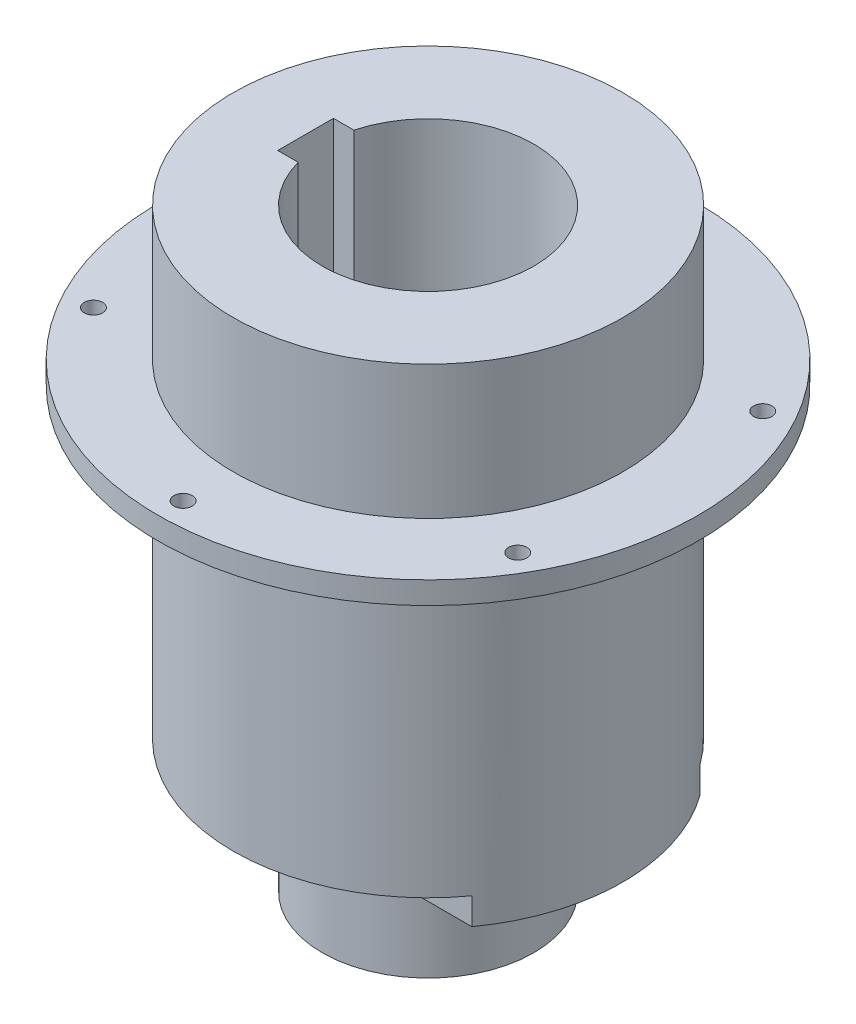
SolidWorks part; units mm, degrees
material "Steel Sectional "
ref_plane "Front Plane" through (0, 0, 0) normal (0, 0, 1) x (1, 0, 0)
ref_plane "Top Plane" through (0, 0, 0) normal (0, 1, 0) x (1, 0, 0)
ref_plane "Right Plane" through (0, 0, 0) normal (1, 0, 0) x (0, 0, -1)
sketch "Sketch1" plane through (0, 0, 0) normal (0, 0, 1) x (1, 0, 0)
  line L0 (0, 0) -> (0, 79.6401) construction
  line L1 (-6.5, 26.3) -> (-19, 26.3)
  line L2 (-19, 26.3) -> (-19, 106.8)
  line L3 (-19, 106.8) -> (-35, 106.8)
  line L4 (-35, 106.8) -> (-35, 19)
  line L5 (-19, 0) -> (-10, 0)
  line L6 (-10, 0) -> (-10, 15)
  line L7 (-10, 15) -> (-6.5, 15)
  line L8 (-6.5, 15) -> (-6.5, 26.3)
  line L9 (-35, 19) -> (-19, 19)
  line L10 (-19, 19) -> (-19, 0)
  dimension "D1" = 70
  dimension "D2" = 38
  dimension "D3" = 13
  dimension "D4" = 20
  dimension "D5" = 15
  dimension "D6" = 106.8
  dimension "D7" = 80.5
  dimension "D8" = 38
  dimension "D9" = 19
revolve "Revolve1" add sketch "Sketch1" angle 360 about L0
sketch "Sketch2" plane through (0, 106.8, 0) normal (0, 1, 0) x (1, 0, 0)
  line L1 (-22, 5) -> (-14, 5)
  line L2 (-22, 5) -> (-22, -5)
  line L3 (-22, -5) -> (-14, -5)
  line L4 (-14, 5) -> (-14, -5)
  line L5 (-22, 5) -> (-14, -5) construction
  line L6 (-22, -5) -> (-14, 5) construction
  circle A2 centre (0, 0) radius 19 construction
  point P0 (-18, 0)
  dimension "D1" = 41
  dimension "D2" = 10
  dimension "D3" = 8
extrude "Extrude1" cut sketch "Sketch2" against normal up to next
sketch "Sketch3" plane through (0, 0, 0) normal (0, 0, 1) x (1, 0, 0)
  line L0 (0, 0) -> (0, 52.8451) construction
  line L1 (-35, 78.8) -> (-48.5, 78.8)
  line L2 (-35, 106.8) -> (-35, 19) construction
  line L3 (-48.5, 78.8) -> (-48.5, 82.8)
  line L4 (-48.5, 82.8) -> (-35, 82.8)
  line L7 (-35, 82.8) -> (-35, 78.8)
  line L8 (35, 106.8) -> (-35, 106.8) construction
  dimension "D1" = 97
  dimension "D3" = 4
  dimension "D5" = 28
revolve "Revolve2" add sketch "Sketch3" angle 360 about L0
sketch "Sketch5" plane through (0, 0, 0) normal (1, 0, 0) x (0, 0, -1)
  line L0 (0, 0) -> (0, 26.3921) construction
  line L1 (20.5, 19) -> (20.5, 23.8)
  line L2 (-36, 19) -> (-20.5, 19)
  line L3 (-36, 19) -> (-36, 23.8)
  line L4 (-36, 23.8) -> (-20.5, 23.8)
  line L5 (-20.5, 19) -> (-20.5, 23.8)
  line L6 (36, 23.8) -> (20.5, 23.8)
  line L7 (36, 19) -> (36, 23.8)
  line L8 (36, 19) -> (20.5, 19)
  line L9 (-35, 78.8) -> (-35, 19) construction
  line L12 (-35, 19) -> (35, 19) construction
  dimension "D1" = 4.8
  dimension "D2" = 41
  dimension "D3" = 1
extrude "Extrude3" cut sketch "Sketch5" against normal mid plane 80
sketch "Sketch6" plane through (0, 82.8, 0) normal (0, 1, 0) x (1, 0, 0)
  circle A0 centre (0, -44) radius 1.65
  circle A1 centre (-38.1051, -22) radius 1.65
  circle A2 centre (-38.1051, 22) radius 1.65
  circle A3 centre (0, 44) radius 1.65
  circle A4 centre (0, 0) radius 44 construction
  circle A5 centre (38.1051, 22) radius 1.65
  circle A6 centre (38.1051, -22) radius 1.65
  point P12 (0, 0)
  dimension "D1" = 3.3
  dimension "D2" = 88
  dimension "D3" = 6
extrude "Extrude4" cut sketch "Sketch6" against normal blind 10
hole_wizard "M8x1.0 Tapped Hole1" positions "Sketch9" profile "Sketch8" tap size "M8x1.0" standard "Ansi Metric"
sketch "Sketch9" plane through (-35, 19, 0) normal (0, -1, 0) x (-1, 0, 0)
  circle A0 centre (-35, 0) radius 27.5
  point P10 (-62.5, 0)
  point P12 (-7.5, 0)
  point P13 (-35, 27.5)
  point P15 (-35, -27.5)
  dimension "D1" = 55
sketch "Sketch8" plane through (27.5, 19, 0) normal (1, 0, 0) x (0, 0, -1)
  line L0 (0, 0) -> (0, 22.103)
  line L1 (0, 22.103) -> (3.5, 20)
  line L2 (3.5, 20) -> (3.5, 0)
  line L5 (3.5, 0) -> (0, 0)
  line L10 (0, 22.103) -> (-3.5, 20) construction
  line L11 (0, -6.35) -> (0, 107.95) construction
  dimension "螺纹孔钻头直径" = 7
  dimension "螺纹孔钻头深度" = 20
  dimension "导头角度" = 118
cosmetic thread "Cosmetic Thread2" parameters "D1"=20, "D2"=8
cosmetic thread "Cosmetic Thread3" parameters "D1"=20, "D2"=8
cosmetic thread "Cosmetic Thread8" parameters "D1"=20, "D2"=8
cosmetic thread "Cosmetic Thread9" parameters "D1"=20, "D2"=8
hole_wizard "M6x1.0 Tapped Hole1" positions "Sketch11" profile "Sketch10" tap size "M6x1.0" standard "Ansi Metric"
sketch "Sketch11" plane through (-22, 0, 0) normal (1, 0, 0) x (0, 0, -1)
  line L0 (35, 106.8) -> (-35, 106.8) construction
  point P0 (0, 56.8)
  dimension "D1" = 50
sketch "Sketch10" plane through (-22, 56.8, 0) normal (0, 1, 0) x (0, 0, -1)
  line L0 (0, 0) -> (0, 26.5)
  line L1 (0, 26.5) -> (2.5, 26.5)
  line L2 (2.5, 26.5) -> (2.5, 0)
  line L5 (2.5, 0) -> (0, 0)
  line L11 (0, -6.35) -> (0, 107.95) construction
  dimension "通孔螺纹孔钻头直径" = 5
  dimension "通孔螺纹孔钻头深度" = 26.5
cosmetic thread "Cosmetic Thread5" parameters "D2"=6
